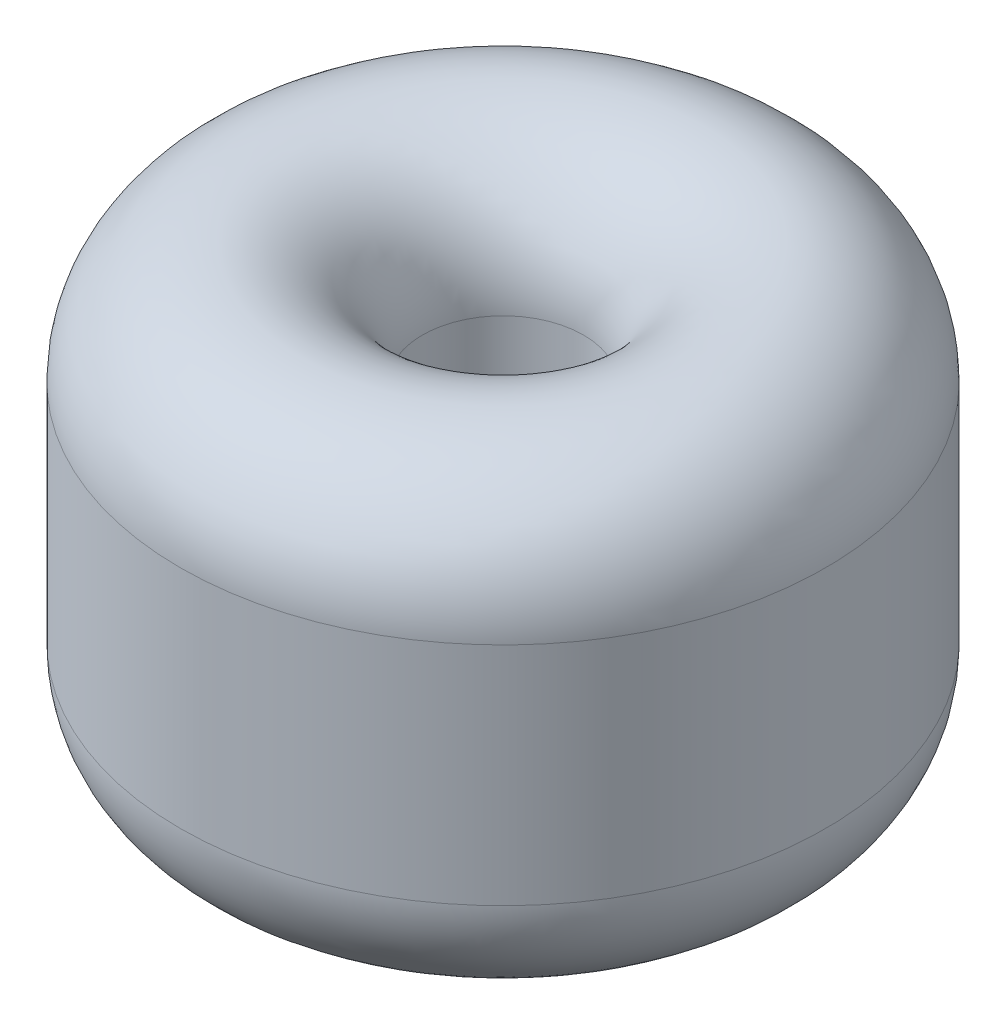
SolidWorks part; units mm, degrees
ref_plane "前视基准面" through (0, 0, 0) normal (0, 0, 1) x (1, 0, 0)
ref_plane "上视基准面" through (0, 0, 0) normal (0, 1, 0) x (1, 0, 0)
ref_plane "右视基准面" through (0, 0, 0) normal (1, 0, 0) x (0, 0, -1)
sketch "草图1" plane through (0, 0, 0) normal (0, 0, 1) x (1, 0, 0)
  line L0 (-40, 14) -> (-40, -14)
  line L1 (-10, 14) -> (-10, -14)
  line L2 (0, 0) -> (0, 49.6653) construction
  arc A0 (-40, 14) -> (-10, 14) centre (-25, 14) cw
  arc A1 (-40, -14) -> (-10, -14) centre (-25, -14) ccw
  dimension "D1" = 30
  dimension "D2" = 10
  dimension "D3" = 28
  dimension "D4" = 14
revolve "旋转1" add sketch "草图1" angle 360 about L2
